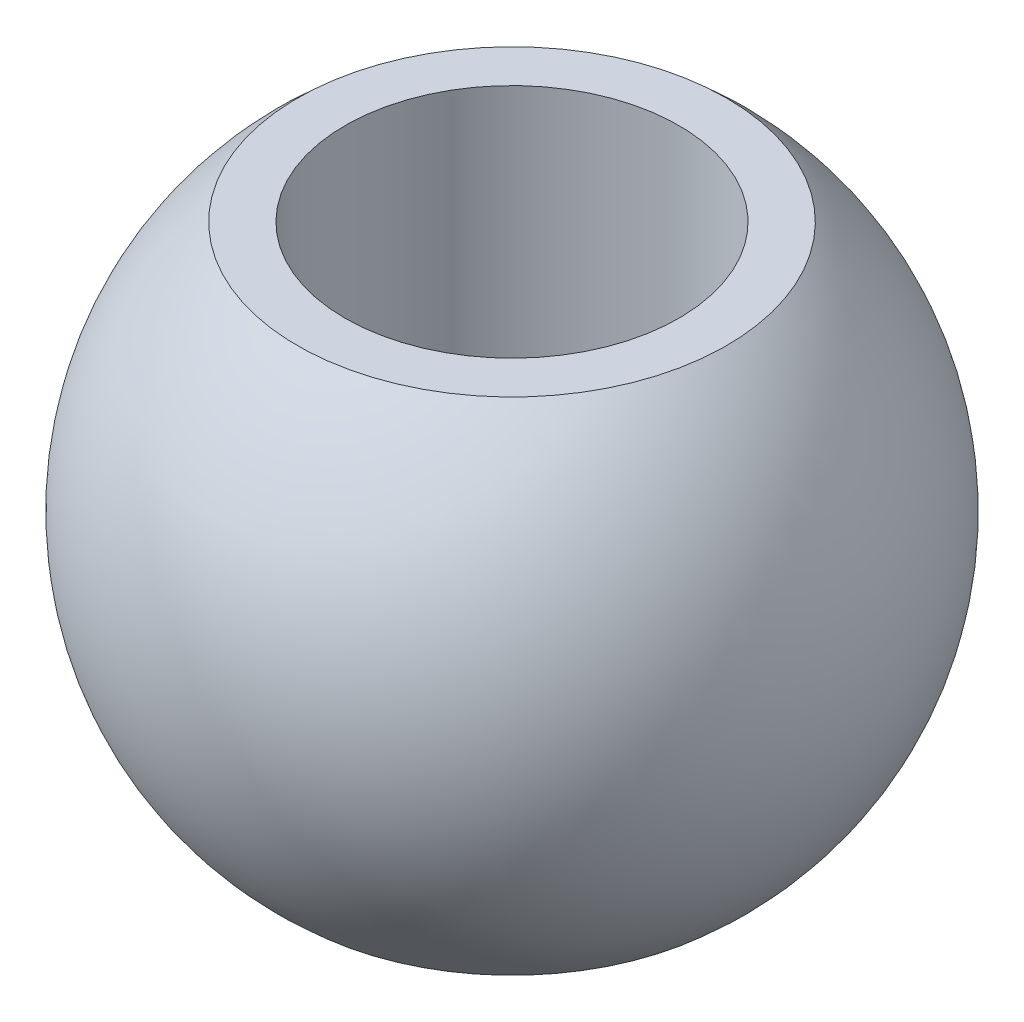
SolidWorks part; units mm, degrees
ref_plane "Front" through (0, 0, 0) normal (0, 0, 1) x (1, 0, 0)
ref_plane "Top" through (0, 0, 0) normal (0, 1, 0) x (1, 0, 0)
ref_plane "Right" through (0, 0, 0) normal (1, 0, 0) x (0, 0, -1)
sketch "Sketch1" plane through (0, 0, 0) normal (0, 0, 1) x (1, 0, 0)
  line L0 (-7.9, 0) -> (7.9, 0)
  arc A0 (7.9, 0) -> (-7.9, 0) centre (0, 0) ccw
  dimension "D1" = 15.8
revolve "Revolve1" add sketch "Sketch1" angle 360 about L0
sketch "Sketch2" plane through (0, 0, 0) normal (0, 0, 1) x (1, 0, 0)
  line L1 (-9.4894, -6) -> (9.4894, -6)
  line L2 (-9.4894, -6) -> (-9.4894, 6)
  line L3 (-9.4894, 6) -> (9.4894, 6)
  line L4 (9.4894, -6) -> (9.4894, 6)
  line L5 (-9.4894, -6) -> (9.4894, 6) construction
  line L6 (-9.4894, 6) -> (9.4894, -6) construction
  line L7 (-9.4894, 6) -> (9.4894, 6)
  line L8 (-9.4894, 6) -> (-9.4894, 8.5022)
  line L9 (-9.4894, 8.5022) -> (9.4894, 8.5022)
  line L10 (9.4894, 6) -> (9.4894, 8.5022)
  line L11 (-9.4894, 6) -> (9.4894, 8.5022) construction
  line L12 (-9.4894, 8.5022) -> (9.4894, 6) construction
  line L13 (9.4894, -6) -> (-9.4894, -6)
  line L14 (9.4894, -6) -> (9.4894, -8.1191)
  line L15 (9.4894, -8.1191) -> (-9.4894, -8.1191)
  line L16 (-9.4894, -6) -> (-9.4894, -8.1191)
  line L17 (9.4894, -6) -> (-9.4894, -8.1191) construction
  line L18 (9.4894, -8.1191) -> (-9.4894, -6) construction
  point P0 (0, 0)
  point P9 (0, 7.2511)
  point P13 (0, -7.0595)
  dimension "D1" = 12
extrude "Cut-Extrude1" cut sketch "Sketch2" against normal mid plane 12 contours L3 L10 L9 L8 | L1 L16 L15 L14
sketch "Sketch3" plane through (0, 6, 0) normal (0, 1, 0) x (1, 0, 0)
  circle A0 centre (0, 0) radius 4
  dimension "D1" = 8
extrude "Cut-Extrude2" cut sketch "Sketch3" against normal through all
